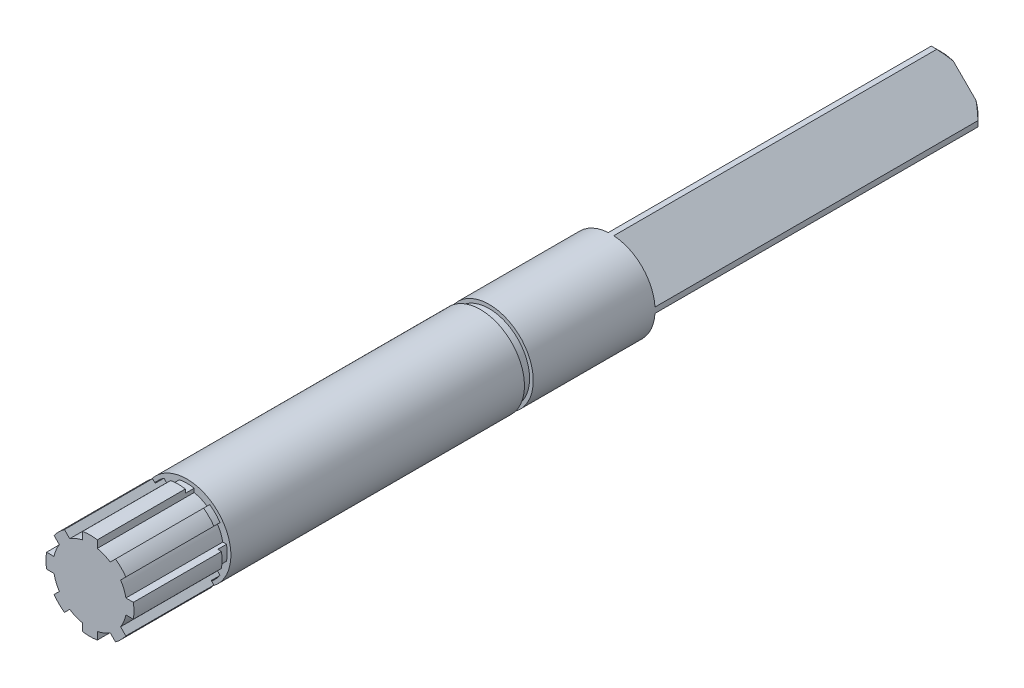
SolidWorks part; units mm, degrees
ref_plane "前视基准面" through (0, 0, 0) normal (0, 0, 1) x (1, 0, 0)
ref_plane "上视基准面" through (0, 0, 0) normal (0, 1, 0) x (1, 0, 0)
ref_plane "右视基准面" through (0, 0, 0) normal (1, 0, 0) x (0, 0, -1)
sketch "草图1" plane through (0, 0, 0) normal (0, 0, 1) x (1, 0, 0)
  circle A0 centre (0, 0) radius 6
  dimension "D1" = 12
extrude "凸台-拉伸1" add sketch "草图1" along normal blind 116
sketch "草图2" plane through (0, 0, 116) normal (0, 0, 1) x (1, 0, 0)
  circle A0 centre (0, 0) radius 5.5
  dimension "D1" = 11
extrude "切除-拉伸1" cut sketch "草图2" along normal blind 1.2 from offset 13.2 flip side to cut offset against normal yes
sketch "草图3" plane through (0, 0, 102.8) normal (0, 0, 1) x (1, 0, 0)
  circle A0 centre (0, 0) radius 5.5
  dimension "D1" = 11
extrude "切除-拉伸2" cut sketch "草图3" against normal blind 1.2 from offset 40 flip side to cut offset against normal yes
sketch "草图4" plane through (0, 0, 116) normal (0, 0, 1) x (1, 0, 0)
  line L0 (-1, 4.899) -> (-1, 5.9161)
  line L1 (1, 4.899) -> (1, 5.9161)
  line L2 (0, -6.6) -> (0, 6.6) construction
  line L3 (2.757, 4.1712) -> (3.4762, 4.8904)
  line L4 (4.1712, 2.757) -> (4.8904, 3.4762)
  line L5 (4.899, 1) -> (5.9161, 1)
  line L6 (4.899, -1) -> (5.9161, -1)
  line L7 (4.1712, -2.757) -> (4.8904, -3.4762)
  line L8 (2.757, -4.1712) -> (3.4762, -4.8904)
  line L9 (1, -4.899) -> (1, -5.9161)
  line L10 (-1, -4.899) -> (-1, -5.9161)
  line L11 (-2.757, -4.1712) -> (-3.4762, -4.8904)
  line L12 (-4.1712, -2.757) -> (-4.8904, -3.4762)
  line L13 (-4.899, -1) -> (-5.9161, -1)
  line L14 (-4.899, 1) -> (-5.9161, 1)
  line L15 (-4.1712, 2.757) -> (-4.8904, 3.4762)
  line L16 (-2.757, 4.1712) -> (-3.4762, 4.8904)
  arc A0 (-1, 4.899) -> (-2.757, 4.1712) centre (0, 0) ccw
  circle A1 centre (0, 0) radius 6 construction
  arc A2 (-1, 5.9161) -> (-3.4762, 4.8904) centre (0, 0) ccw
  arc A3 (-4.1712, 2.757) -> (-4.899, 1) centre (0, 0) ccw
  arc A4 (-4.8904, 3.4762) -> (-5.9161, 1) centre (0, 0) ccw
  arc A5 (-4.899, -1) -> (-4.1712, -2.757) centre (0, 0) ccw
  arc A6 (-5.9161, -1) -> (-4.8904, -3.4762) centre (0, 0) ccw
  arc A7 (-2.757, -4.1712) -> (-1, -4.899) centre (0, 0) ccw
  arc A8 (-3.4762, -4.8904) -> (-1, -5.9161) centre (0, 0) ccw
  arc A9 (1, -4.899) -> (2.757, -4.1712) centre (0, 0) ccw
  arc A10 (1, -5.9161) -> (3.4762, -4.8904) centre (0, 0) ccw
  arc A11 (4.1712, -2.757) -> (4.899, -1) centre (0, 0) ccw
  arc A12 (4.8904, -3.4762) -> (5.9161, -1) centre (0, 0) ccw
  arc A13 (5.9161, 1) -> (4.8904, 3.4762) centre (0, 0) ccw
  arc A14 (4.899, 1) -> (4.1712, 2.757) centre (0, 0) ccw
  arc A15 (2.757, 4.1712) -> (1, 4.899) centre (0, 0) ccw
  arc A16 (3.4762, 4.8904) -> (1, 5.9161) centre (0, 0) ccw
  dimension "D1" = 10
  dimension "D2" = 1
  dimension "D3" = 1
  dimension "D4" = 8
extrude "切除-拉伸3" cut sketch "草图4" against normal blind 13.2
chamfer "倒角1" distance 1 angle 45 1 edges at (6, 0, 0)
sketch "草图5" plane through (0, 0, 0) normal (0, 0, -1) x (-1, 0, 0)
  line L0 (0, -6.364) -> (6.364, 0)
  line L1 (0, -6.364) -> (-6.364, 0)
  line L2 (6.364, 0) -> (0, 6.364)
  line L3 (-6.364, 0) -> (0, 6.364)
  line L4 (0, -6.364) -> (0, 6.364) construction
  line L5 (6.364, 0) -> (-6.364, 0) construction
  line L6 (0, 6.6) -> (0, -6.6) construction
  line L7 (6.6, 0) -> (-6.6, 0) construction
  point P1 (0, 0)
  dimension "D1" = 9
extrude "切除-拉伸4" cut sketch "草图5" against normal blind 45 flip side to cut
